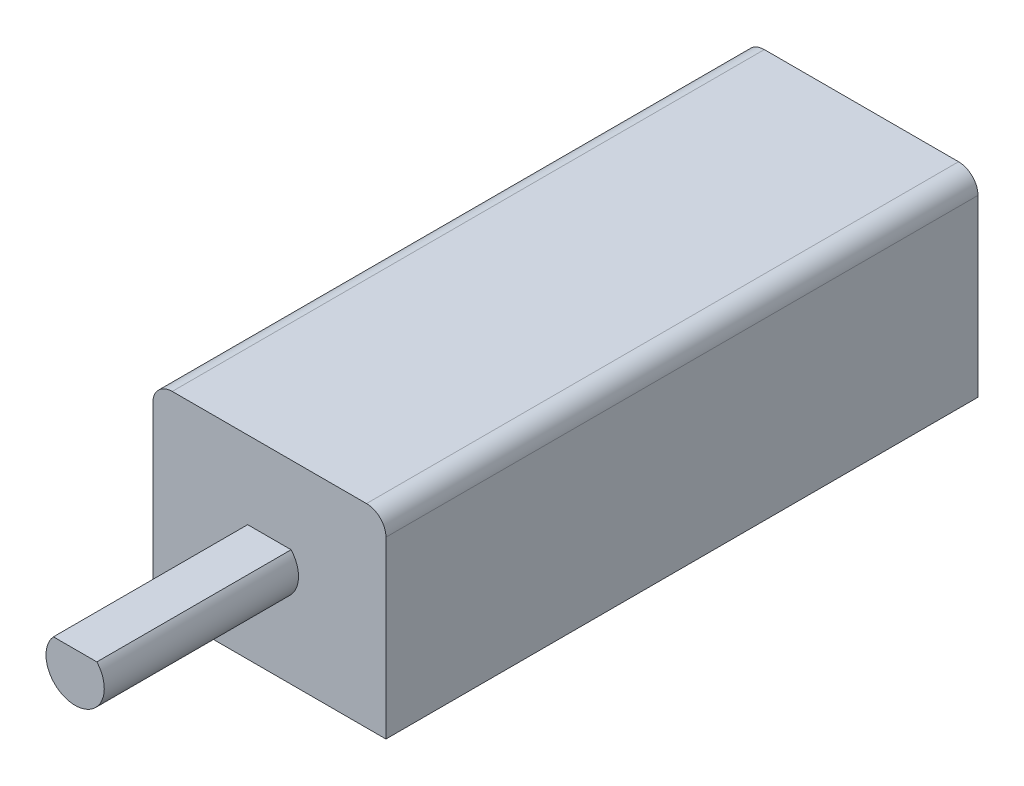
SolidWorks part; units mm, degrees
ref_plane "Front Plane" through (0, 0, 0) normal (0, 0, 1) x (1, 0, 0)
ref_plane "Top Plane" through (0, 0, 0) normal (0, 1, 0) x (1, 0, 0)
ref_plane "Right Plane" through (0, 0, 0) normal (1, 0, 0) x (0, 0, -1)
sketch "Sketch1" plane through (0, 0, 0) normal (0, 0, 1) x (1, 0, 0)
  line L1 (-6, -5) -> (6, -5)
  line L2 (-6, -5) -> (-6, 5)
  line L3 (-6, 5) -> (6, 5)
  line L4 (6, -5) -> (6, 5)
  line L5 (-6, -5) -> (6, 5) construction
  line L6 (-6, 5) -> (6, -5) construction
  point P0 (0, 0)
  dimension "D1" = 12
  dimension "D2" = 10
extrude "Boss-Extrude1" add sketch "Sketch1" against normal blind 40.48
sketch "Sketch2" plane through (0, 0, 0) normal (0, 0, 1) x (1, 0, 0)
  line L1 (-8.8819, 0) -> (12.5133, 0) construction
  line L2 (-8.8819, -1.5) -> (12.5133, -1.5) construction
  line L3 (-1.118, 1) -> (1.118, 1)
  line L5 (0, 1) -> (0, -7.3553) construction
  arc A0 (-1.118, 1) -> (1.118, 1) centre (0, 0) ccw
  dimension "D2" = 3
  dimension "D1" = 2.5
extrude "Cut-Extrude1" cut sketch "Sketch2" against normal blind 10 flip side to cut
fillet "Fillet1" radius 1 2 edges at (6, 5, -25.24) (-6, 5, -25.24)
